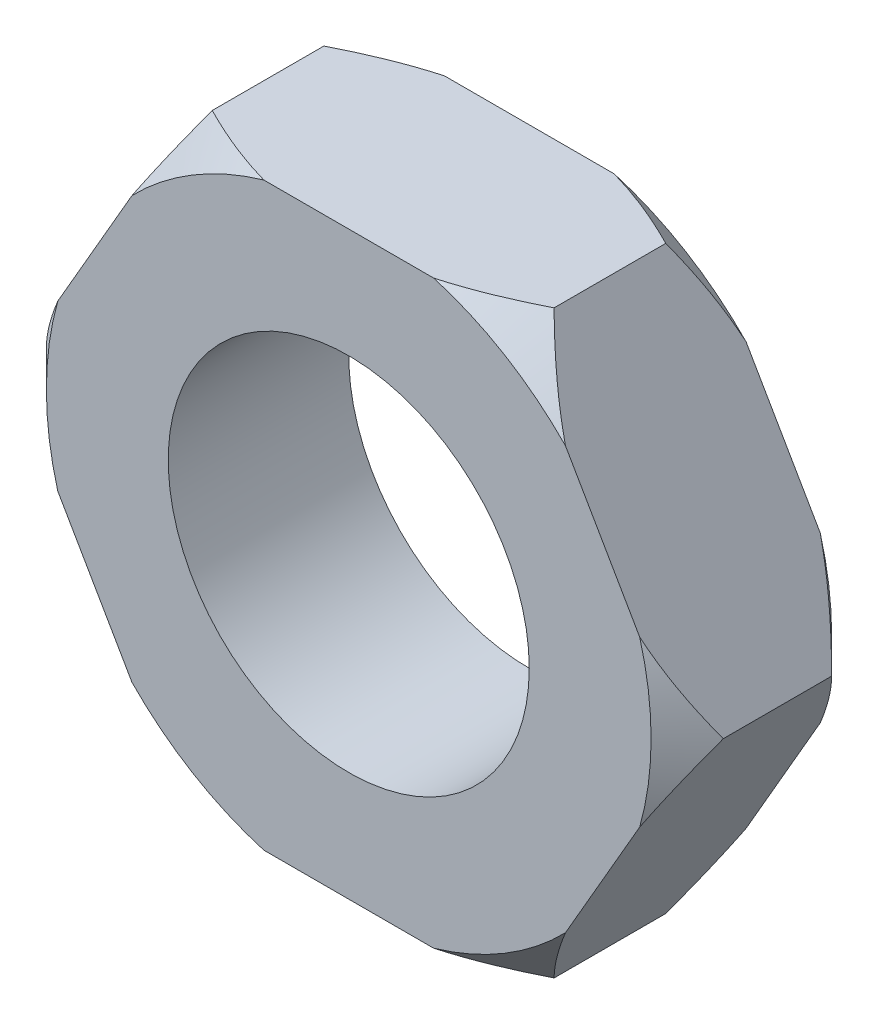
SolidWorks part; units mm, degrees
ref_plane "Plan1" through (0, 0, 0) normal (0, 0, 1) x (1, 0, 0)
ref_plane "Plan2" through (0, 0, 0) normal (0, 1, 0) x (1, 0, 0)
ref_plane "Plan3" through (0, 0, 0) normal (1, 0, 0) x (0, 0, -1)
sketch "Esquisse1" plane through (0, 0, 0) normal (0, 0, 1) x (1, 0, 0)
  circle A0 centre (0, 0) radius 7.5
  circle A1 centre (0, 0) radius 4
  dimension "D1" = 15
  dimension "D2" = 8
extrude "Base-Extrusion" add sketch "Esquisse1" along normal blind 4
chamfer "Chanfrein1" distance 0.8 angle 45
sketch "Esquisse2" plane through (0, 0, 4) normal (0, 0, 1) x (1, 0, 0)
  line L0 (-7.5, 0) -> (-3.7875, 6.4303)
  line L2 (-7.5, 0) -> (8, 0) construction
  line L3 (-3.7875, 6.4303) -> (3.7875, 6.4303)
  line L4 (0, 0) -> (0, 8) construction
  line L5 (7.5, 0) -> (3.7875, 6.4303)
  line L6 (-3.7875, -6.4303) -> (3.7875, -6.4303)
  line L7 (-7.5, 0) -> (-3.7875, -6.4303)
  line L8 (7.5, 0) -> (3.7875, -6.4303)
  line L9 (-9, 9) -> (9, 9)
  line L10 (-9, 9) -> (-9, -9)
  line L11 (9, -9) -> (-9, -9)
  line L12 (9, -9) -> (9, 9)
  circle A0 centre (0, 0) radius 7.5 construction
  dimension "D1" = 60
extrude "Enlèv. mat.-Extru.1" cut sketch "Esquisse2" against normal blind 4
